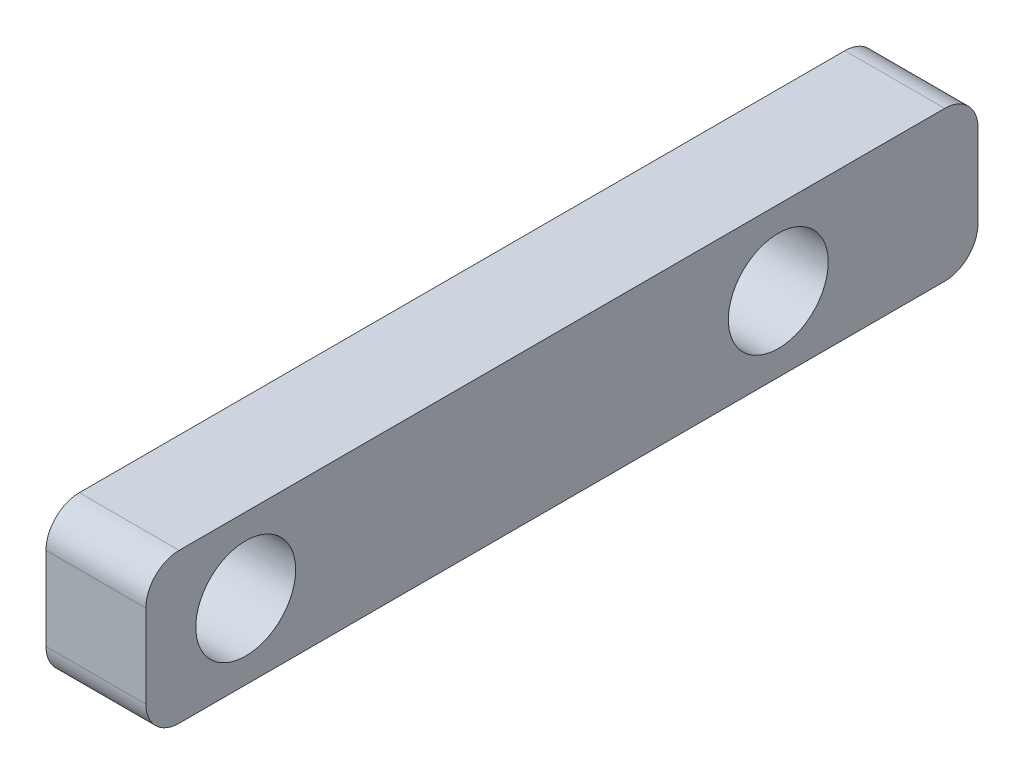
SolidWorks part; units mm, degrees
ref_plane "Alzado" through (0, 0, 0) normal (0, 0, 1) x (1, 0, 0)
ref_plane "Planta" through (0, 0, 0) normal (0, 1, 0) x (1, 0, 0)
ref_plane "Vista lateral" through (0, 0, 0) normal (1, 0, 0) x (0, 0, -1)
sketch "Croquis1" plane through (0, 0, 0) normal (1, 0, 0) x (0, 0, -1)
  line L0 (-11.5, 2.25) -> (11.5, 2.25)
  line L2 (-12.5, 0) -> (12.5, 0) construction
  line L3 (-12.5, 1.25) -> (-12.5, -1.25)
  line L4 (-11.5, -2.25) -> (11.5, -2.25)
  line L5 (12.5, 1.25) -> (12.5, -1.25)
  arc A0 (-12.5, -1.25) -> (-11.5, -2.25) centre (-11.5, -1.25) ccw
  arc A1 (-12.5, 1.25) -> (-11.5, 2.25) centre (-11.5, 1.25) cw
  arc A2 (11.5, -2.25) -> (12.5, -1.25) centre (11.5, -1.25) ccw
  arc A3 (11.5, 2.25) -> (12.5, 1.25) centre (11.5, 1.25) cw
  point P1 (0, 0)
  point P9 (-12.5, -2.25)
  point P13 (-12.5, 2.25)
  point P16 (12.5, -2.25)
  point P19 (12.5, 2.25)
  dimension "D3" = 1
  dimension "D4" = 1
  dimension "D1" = 2.25
  dimension "D2" = 25
extrude "Saliente-Extruir1" add sketch "Croquis1" along normal mid plane 3
sketch "Croquis2" plane through (0, 0, 0) normal (1, 0, 0) x (0, 0, -1)
  line L0 (-12.5, 1.25) -> (-12.5, -1.25) construction
  line L1 (12.5, -1.25) -> (12.5, 1.25) construction
  circle A0 centre (-9.5, 0) radius 1.5
  circle A1 centre (6.5, 0) radius 1.5
  dimension "D1" = 3
  dimension "D3" = 3
  dimension "D2" = 3
  dimension "D4" = 6
extrude "Cortar-Extruir1" cut sketch "Croquis2" against normal through all both and the other way through all
